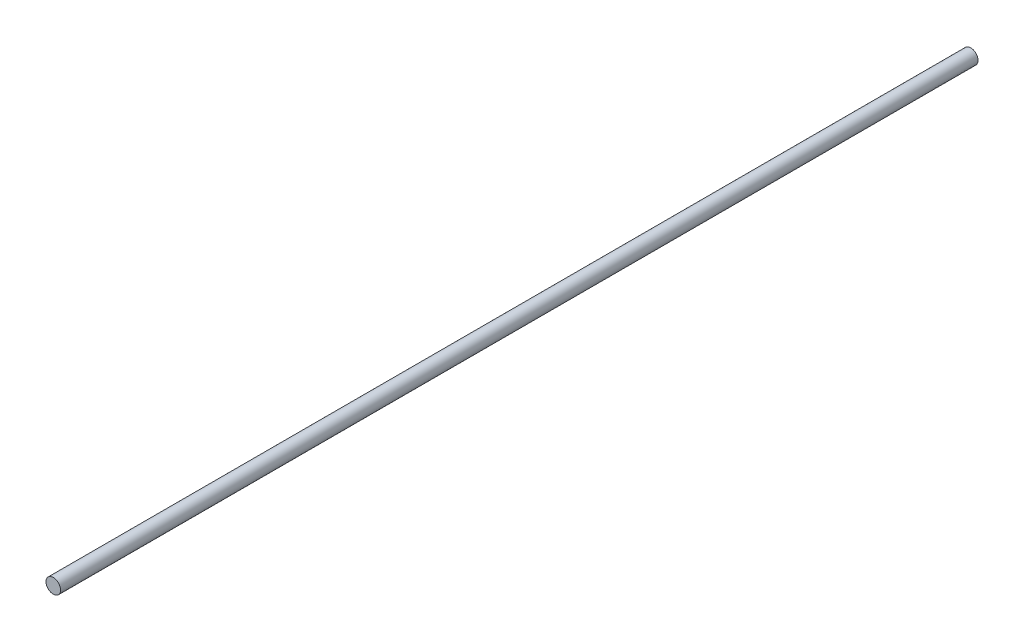
SolidWorks part; units mm, degrees
material "Thornel Mat VMA"
ref_plane "Front Plane" through (0, 0, 0) normal (0, 0, 1) x (1, 0, 0)
ref_plane "Top Plane" through (0, 0, 0) normal (0, 1, 0) x (1, 0, 0)
ref_plane "Right Plane" through (0, 0, 0) normal (1, 0, 0) x (0, 0, -1)
sketch "Sketch1" plane through (0, 0, 0) normal (0, 0, 1) x (1, 0, 0)
  circle A0 centre (0, 0) radius 3.175
  dimension "D1" = 6.35
extrude "Boss-Extrude1" add sketch "Sketch1" along normal mid plane 400.05
